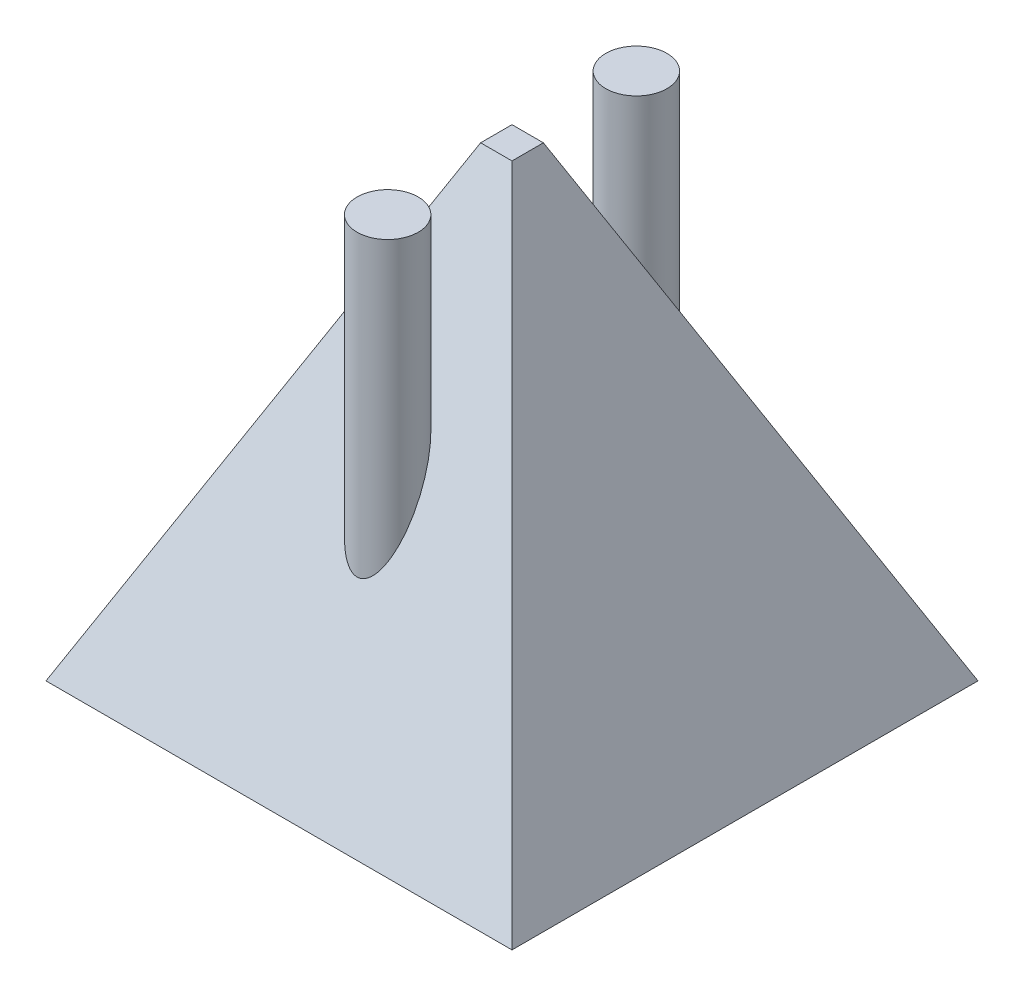
SolidWorks part; units mm, degrees
ref_plane "Front Plane" through (0, 0, 0) normal (0, 0, 1) x (1, 0, 0)
ref_plane "Top Plane" through (0, 0, 0) normal (0, 1, 0) x (1, 0, 0)
ref_plane "Right Plane" through (0, 0, 0) normal (1, 0, 0) x (0, 0, -1)
sketch "Sketch1" plane through (0, 0, 0) normal (0, 1, 0) x (1, 0, 0)
  line L1 (-19.05, 19.05) -> (19.05, 19.05)
  line L2 (-19.05, 19.05) -> (-19.05, -19.05)
  line L3 (-19.05, -19.05) -> (19.05, -19.05)
  line L4 (19.05, 19.05) -> (19.05, -19.05)
  line L5 (-19.05, 19.05) -> (19.05, -19.05) construction
  line L6 (-19.05, -19.05) -> (19.05, 19.05) construction
  point P0 (0, 0)
  dimension "D1" = 38.1
extrude "Boss-Extrude1" add sketch "Sketch1" along normal mid plane 38.1
draft "Draft1" type of draft neutral plane draft angle 25 faces to draft 4 face at (-19.05, 0, 0) face at (0, 0, 19.05) face at (19.05, 0, 0) face at (0, 0, -19.05) neutral plane through (0, -19.05, 0) neutral plane normal (0, -1, 0) reverse direction yes parameters "D1"=25
sketch "Sketch2" plane through (0, 0, 0) normal (0, 1, 0) x (1, 0, 0)
  line L0 (0, 19.05) -> (0, 1.2837) construction
  line L1 (19.05, 19.05) -> (-19.05, 19.05) construction
  line L2 (1.2837, 1.2837) -> (-1.2837, 1.2837) construction
  line L3 (0, -1.2837) -> (0, -19.05) construction
  line L4 (-1.2837, -1.2837) -> (1.2837, -1.2837) construction
  line L5 (-19.05, -19.05) -> (19.05, -19.05) construction
  line L6 (-19.05, 0) -> (19.05, 0) construction
  line L7 (-19.05, 19.05) -> (-19.05, -19.05) construction
  line L8 (19.05, -19.05) -> (19.05, 19.05) construction
  circle A0 centre (0, 10.1668) radius 2.5
  circle A1 centre (0, -10.1668) radius 2.5
  point P19 (19.05, 0)
  dimension "D1" = 5
extrude "Boss-Extrude3" add sketch "Sketch2" along normal mid plane 38.1
